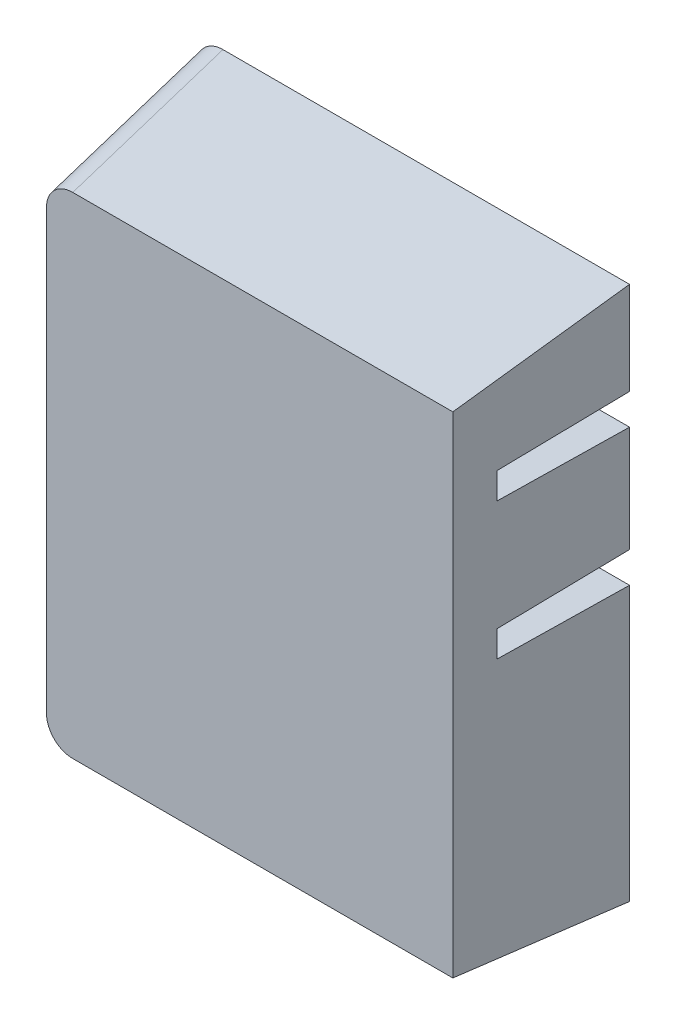
SolidWorks part; units mm, degrees
ref_plane "Plan de face" through (0, 0, 0) normal (0, 0, 1) x (1, 0, 0)
ref_plane "Plan de dessus" through (0, 0, 0) normal (0, 1, 0) x (1, 0, 0)
ref_plane "Plan de droite" through (0, 0, 0) normal (1, 0, 0) x (0, 0, -1)
sketch "Esquisse1" plane through (0, 0, 0) normal (0, 0, 1) x (1, 0, 0)
  line L1 (-23, 27.75) -> (23, 27.75)
  line L2 (-23, 27.75) -> (-23, -27.75)
  line L3 (-23, -27.75) -> (23, -27.75)
  line L4 (23, 27.75) -> (23, -27.75)
  line L5 (-23, 27.75) -> (23, -27.75) construction
  line L6 (-23, -27.75) -> (23, 27.75) construction
  point P0 (0, 0)
  dimension "D1" = 46
  dimension "D2" = 55.5
ref_plane "Plan1" through (0, 0, -20) normal (0, 0, 1) x (1, 0, 0)
sketch "Esquisse2" plane through (0, 0, -20) normal (0, 0, 1) x (1, 0, 0)
  line L0 (-23, 27.75) -> (-23, -27.75) construction
  line L1 (-26, 30.25) -> (23, 30.25)
  line L2 (-26, 30.25) -> (-26, -30.25)
  line L3 (-26, -30.25) -> (23, -30.25)
  line L4 (23, 30.25) -> (23, -30.25)
  line L5 (-26, 30.25) -> (23, -30.25) construction
  line L6 (-26, -30.25) -> (23, 30.25) construction
  line L7 (-23, 27.75) -> (23, 27.75) construction
  line L9 (23, 27.75) -> (23, -27.75) construction
  dimension "D1" = 60.5
  dimension "D2" = 60.5
  dimension "D3" = 3
  dimension "D4" = 2.5
  dimension "D5" = 0
  dimension "D6" = 49
loft "Lissage1" add profiles "Esquisse1", "Esquisse2"
ref_plane "Plan2" through (0, 0, -20) normal (0, 0, 1) x (1, 0, 0)
sketch "Esquisse3" plane through (0, 0, -20) normal (0, 0, 1) x (1, 0, 0)
  line L0 (-31.1432, 0.75) -> (29.2814, 0.75)
  line L1 (-32.7508, 16.25) -> (27.6739, 16.25)
  line L2 (-32.7508, 16.25) -> (-32.7508, 19.75)
  line L3 (-32.7508, 19.75) -> (27.6739, 19.75)
  line L4 (27.6739, 16.25) -> (27.6739, 19.75)
  line L5 (-32.7508, 16.25) -> (27.6739, 19.75) construction
  line L6 (-32.7508, 19.75) -> (27.6739, 16.25) construction
  line L7 (-31.1432, 0.75) -> (-31.1432, 4.25)
  line L8 (-31.1432, 4.25) -> (29.2814, 4.25)
  line L9 (29.2814, 0.75) -> (29.2814, 4.25)
  line L10 (-31.1432, 0.75) -> (29.2814, 4.25) construction
  line L11 (-31.1432, 4.25) -> (29.2814, 0.75) construction
  line L12 (23, 27.75) -> (-23, 27.75) construction
  line L13 (23, -27.75) -> (23, 27.75) construction
  line L14 (-21, -17.45) -> (21, -17.45)
  line L15 (-21, -17.45) -> (-21, -14.25)
  line L16 (-21, -14.25) -> (21, -14.25)
  line L17 (21, -17.45) -> (21, -14.25)
  line L18 (-21, -17.45) -> (21, -14.25) construction
  line L19 (-21, -14.25) -> (21, -17.45) construction
  point P0 (-2.5385, 18)
  point P5 (-0.9309, 2.5)
  point P12 (0, -15.85)
  dimension "D1" = 3.5
  dimension "D2" = 3.5
  dimension "D3" = 8
  dimension "D4" = 12
  dimension "D5" = 3.2
  dimension "D6" = 15
  dimension "D7" = 42
  dimension "D8" = 2
extrude "Enlèv. mat.-Extru.3" cut sketch "Esquisse3" along normal blind 15 draft 1
fillet "Congé1" radius 3 2 edges
